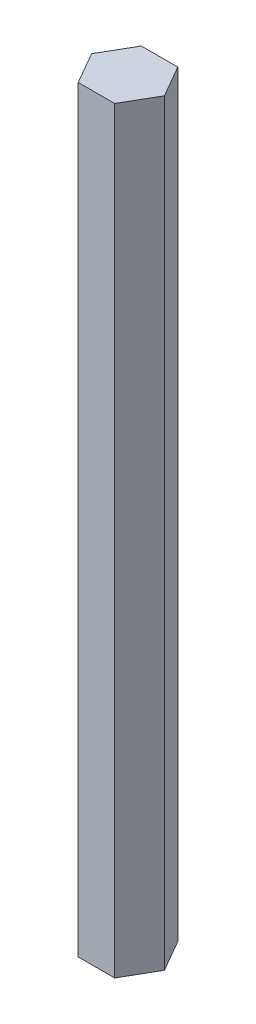
SolidWorks part; units mm, degrees
ref_plane "Front Plane" through (0, 0, 0) normal (0, 0, 1) x (1, 0, 0)
ref_plane "Top Plane" through (0, 0, 0) normal (0, 1, 0) x (1, 0, 0)
ref_plane "Right Plane" through (0, 0, 0) normal (1, 0, 0) x (0, 0, -1)
sketch "Sketch1" plane through (0, 0, 0) normal (0, 1, 0) x (1, 0, 0)
  line L1 (7.3323, 0) -> (3.6662, 6.35)
  line L2 (3.6662, 6.35) -> (-3.6662, 6.35)
  line L3 (-3.6662, 6.35) -> (-7.3323, 0)
  line L4 (-7.3323, 0) -> (-3.6662, -6.35)
  line L5 (-3.6662, -6.35) -> (3.6662, -6.35)
  line L6 (3.6662, -6.35) -> (7.3323, 0)
  circle A0 centre (0, 0) radius 6.35 construction
  dimension "D1" = 12.7
extrude "Boss-Extrude1" add sketch "Sketch1" along normal blind 152.4
